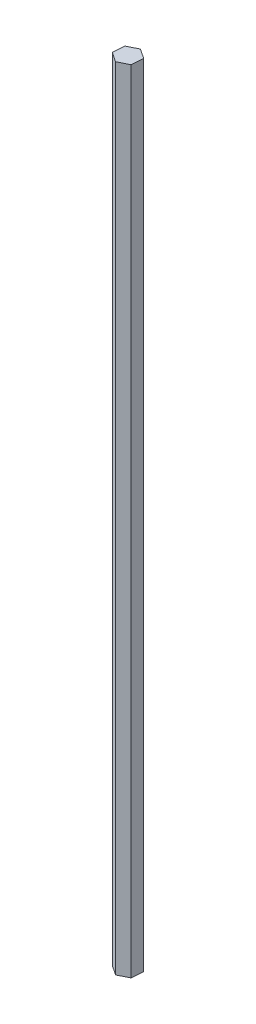
SolidWorks part; units mm, degrees
ref_plane "Front Plane" through (0, 0, 0) normal (0, 0, 1) x (1, 0, 0)
ref_plane "Top Plane" through (0, 0, 0) normal (0, 1, 0) x (1, 0, 0)
ref_plane "Right Plane" through (0, 0, 0) normal (1, 0, 0) x (0, 0, -1)
sketch "Sketch1" plane through (0, 0, 0) normal (0, 1, 0) x (1, 0, 0)
  line L1 (6.0978, -4.072) -> (6.5753, 3.2448)
  line L2 (6.5753, 3.2448) -> (0.4775, 7.3168)
  line L3 (0.4775, 7.3168) -> (-6.0978, 4.072)
  line L4 (-6.0978, 4.072) -> (-6.5753, -3.2448)
  line L5 (-6.5753, -3.2448) -> (-0.4775, -7.3168)
  line L6 (-0.4775, -7.3168) -> (6.0978, -4.072)
  circle A0 centre (0, 0) radius 6.35 construction
  dimension "D1" = 12.7
extrude "Boss-Extrude1" add sketch "Sketch1" along normal mid plane 495.3
